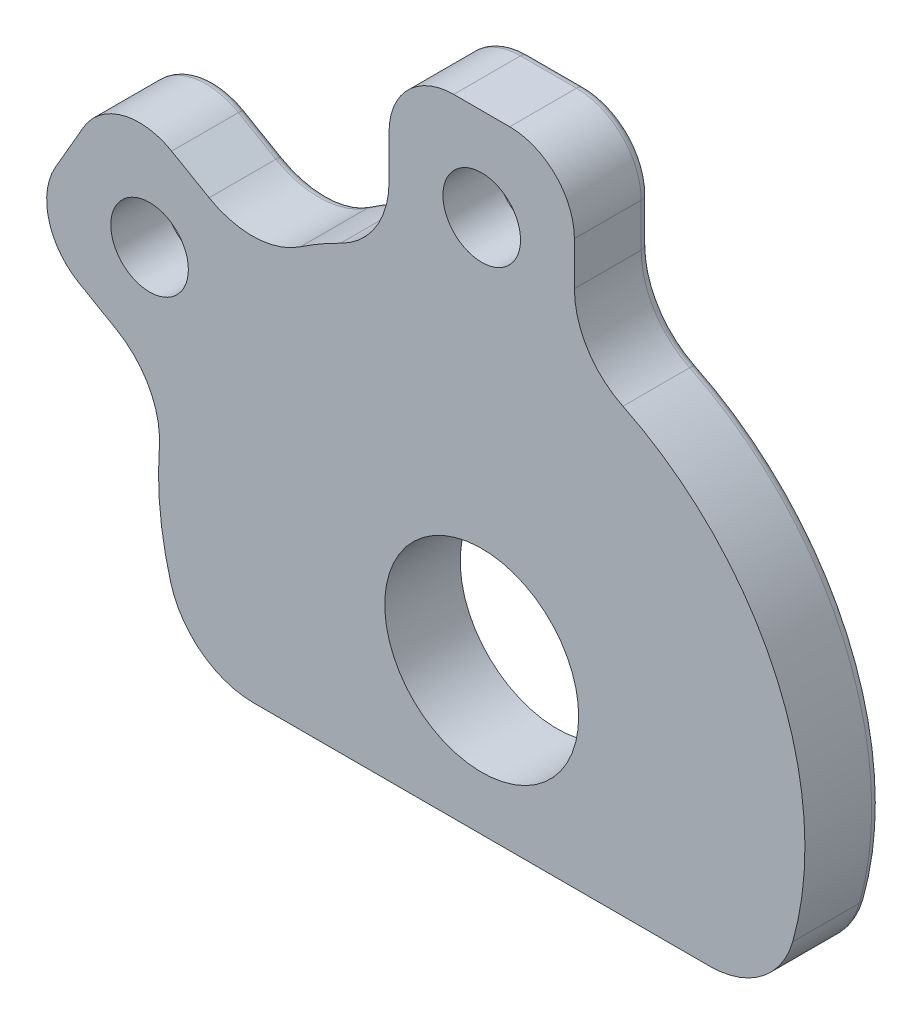
SolidWorks part; units mm, degrees
material "ABS"
ref_plane "Front Plane" through (0, 0, 0) normal (0, 0, 1) x (1, 0, 0)
ref_plane "Top Plane" through (0, 0, 0) normal (0, 1, 0) x (1, 0, 0)
ref_plane "Right Plane" through (0, 0, 0) normal (1, 0, 0) x (0, 0, -1)
sketch "Sketch10" plane through (0, 0, 0) normal (0, 0, 1) x (1, 0, 0)
  line L0 (-13.2665, -7) -> (13.2665, -7)
  arc A0 (13.2665, -7) -> (-13.2665, -7) centre (0, 0) ccw
  circle A1 centre (0, 0) radius 4.5
  dimension "D1" = 30
  dimension "D2" = 9
  dimension "D3" = 2.5
extrude "Boss-Extrude6" add sketch "Sketch10" along normal mid plane 3.5
sketch "Sketch13" plane through (0, 0, 0) normal (0, 0, 1) x (1, 0, 0)
  line L3 (-4.3, 14.3705) -> (-4.3, 19.1)
  line L10 (-1.3, 22.1) -> (1.3, 22.1)
  line L11 (4.3, 19.1) -> (4.3, 14.3705)
  line L12 (-14.5952, 3.4613) -> (-18.6911, 5.8261)
  line L13 (-19.7892, 9.9242) -> (-18.4892, 12.1758)
  line L14 (-14.3911, 13.2739) -> (-10.2952, 10.9091)
  line L15 (0, 0) -> (4.3, 14.3705) construction
  line L16 (0, 0) -> (-10.2952, 10.9091) construction
  arc A13 (13.2665, -7) -> (-13.2665, -7) centre (0, 0) ccw construction
  arc A14 (4.3, 14.3705) -> (-4.3, 14.3705) centre (0, 0) ccw
  circle A15 centre (0, 17.8) radius 1.5 construction
  circle A16 centre (0, 17.8) radius 1.8
  arc A17 (1.3, 22.1) -> (4.3, 19.1) centre (1.3, 19.1) cw
  arc A18 (-4.3, 19.1) -> (-1.3, 22.1) centre (-1.3, 19.1) cw
  arc A19 (-10.2952, 10.9091) -> (-14.5952, 3.4613) centre (0, 0) ccw
  circle A20 centre (-15.4153, 8.9) radius 1.8
  arc A21 (-18.4892, 12.1758) -> (-14.3911, 13.2739) centre (-15.8911, 10.6758) cw
  arc A22 (-18.6911, 5.8261) -> (-19.7892, 9.9242) centre (-17.1911, 8.4242) cw
  circle A23 centre (-15.4153, 8.9) radius 1.5 construction
  point P5 (0, 22.1)
  dimension "D1" = 3
  dimension "D3" = 2.5
  dimension "D4" = 2.5
  dimension "D5" = 1
  dimension "D6" = 3
  dimension "D8" = 60
  dimension "D2" = 0.3
  dimension "D7" = 2
extrude "Boss-Extrude7" add sketch "Sketch13" along normal mid plane 3.5
fillet "Fillet1" radius 4 6 edges at (13.2665, -7, 0) (-13.2665, -7, 0) (-14.5952, 3.4613, 0) (4.3, 14.3705, 0) (-10.2952, 10.9091, 0) (-4.3, 14.3705, 0)
sketch "Sketch15" plane through (0, 0, -1.75) normal (0, 0, -1) x (-1, 0, 0)
  line L9 (6.4913, 4.9501) -> (7.1252, 6.3095) construction
  line L10 (7.1252, 6.3095) -> (3.5, 8) construction
  line L11 (3.5, 8) -> (2.8661, 6.6405) construction
  line L12 (2.8661, 6.6405) -> (6.4913, 4.9501) construction
  line L13 (-3.5, 8) -> (-7.1252, 6.3095) construction
  line L14 (-7.1252, 6.3095) -> (-6.4913, 4.9501) construction
  line L15 (-6.4913, 4.9501) -> (-2.8661, 6.6405) construction
  line L16 (-2.8661, 6.6405) -> (-3.5, 8) construction
  line L17 (6.4913, 4.9501) -> (7.1252, 6.3095) construction
  line L18 (7.1252, 6.3095) -> (3.5, 8) construction
  line L19 (3.5, 8) -> (2.8661, 6.6405) construction
  line L20 (2.8661, 6.6405) -> (6.4913, 4.9501) construction
  line L21 (-3.5, 8) -> (-7.1252, 6.3095) construction
  line L22 (-7.1252, 6.3095) -> (-6.4913, 4.9501) construction
  line L23 (-6.4913, 4.9501) -> (-2.8661, 6.6405) construction
  line L24 (-2.8661, 6.6405) -> (-3.5, 8) construction
  line L25 (-3.7113, 8.4532) -> (-7.3365, 6.7627)
  line L26 (-7.5784, 6.0982) -> (-6.9445, 4.7388)
  line L27 (-6.28, 4.4969) -> (-2.6548, 6.1874)
  line L28 (-2.4129, 6.8518) -> (-3.0468, 8.2113)
  line L29 (6.9445, 4.7388) -> (7.5784, 6.0982)
  line L30 (7.3365, 6.7627) -> (3.7113, 8.4532)
  line L31 (3.0468, 8.2113) -> (2.4129, 6.8518)
  line L32 (2.6548, 6.1874) -> (6.28, 4.4969)
  line L33 (6.7331, 4.2856) -> (7.7897, 6.5514) construction
  line L34 (7.7897, 6.5514) -> (3.2582, 8.6645) construction
  line L35 (2.2016, 6.3987) -> (6.7331, 4.2856) construction
  line L36 (3.2582, 8.6645) -> (2.2016, 6.3987) construction
  line L37 (-7.7897, 6.5514) -> (-6.7331, 4.2856) construction
  line L38 (-6.7331, 4.2856) -> (-2.2016, 6.3987) construction
  line L39 (-3.2582, 8.6645) -> (-7.7897, 6.5514) construction
  line L40 (-2.2016, 6.3987) -> (-3.2582, 8.6645) construction
  arc A0 (7.5784, 6.0982) -> (7.3365, 6.7627) centre (7.1252, 6.3095) ccw
  arc A1 (6.9445, 4.7388) -> (6.28, 4.4969) centre (6.4913, 4.9501) cw
  arc A2 (2.4129, 6.8518) -> (2.6548, 6.1874) centre (2.8661, 6.6405) ccw
  arc A3 (3.7113, 8.4532) -> (3.0468, 8.2113) centre (3.5, 8) ccw
  arc A4 (-6.9445, 4.7388) -> (-6.28, 4.4969) centre (-6.4913, 4.9501) ccw
  arc A5 (-7.3365, 6.7627) -> (-7.5784, 6.0982) centre (-7.1252, 6.3095) ccw
  arc A6 (-2.6548, 6.1874) -> (-2.4129, 6.8518) centre (-2.8661, 6.6405) ccw
  arc A7 (-3.7113, 8.4532) -> (-3.0468, 8.2113) centre (-3.5, 8) cw
  dimension "D2" = 0.5
  dimension "D1" = 0.5
extrude "Cut-Extrude2" cut sketch "Sketch15" against normal blind 1.5
sketch "Sketch16" plane through (0, 0, -1.75) normal (0, 0, -1) x (-1, 0, 0)
  line L0 (0, 0) -> (0, 17.8) construction
  line L1 (0, 0) -> (15.4153, 8.9) construction
  circle A0 centre (0, 17.8) radius 1.8 construction
  circle A1 centre (0, 17.8) radius 3
  circle A3 centre (15.4153, 8.9) radius 3
  dimension "D1" = 6
  dimension "D3" = 60
  dimension "D2" = 2
extrude "Cut-Extrude3" cut sketch "Sketch16" against normal blind 1
chamfer "Chamfer1" distance 0.5 angle 45 2 edges at (-18.4153, 8.9, -1.75) (-3, 17.8, -1.75)
fillet "Fillet2" radius 0.4 20 edges at (12.9951, -6.1909, -1.75) (0, -7, -1.75) (-12.9951, -6.1909, -1.75) (-14.9215, -1.5327, -1.75) (13.6887, 6.1334, -1.75) (-15.418, 3.2325, -1.75) (-17.8213, 5.3239, -1.75) (-20.0889, 7.6477, -1.75) (-19.1392, 11.05, -1.75) (-16.6675, 13.5736, -1.75) (-13.5213, 12.7717, -1.75) (-10.5084, 11.7362, -1.75) (-7.5, 12.9904, -1.75) (-4.9096, 14.9687, -1.75) (-4.3, 18.0956, -1.75) (-3.4213, 21.2213, -1.75) (0, 22.1, -1.75) (3.4213, 21.2213, -1.75) (4.3, 18.0956, -1.75) (4.9096, 14.9687, -1.75)
